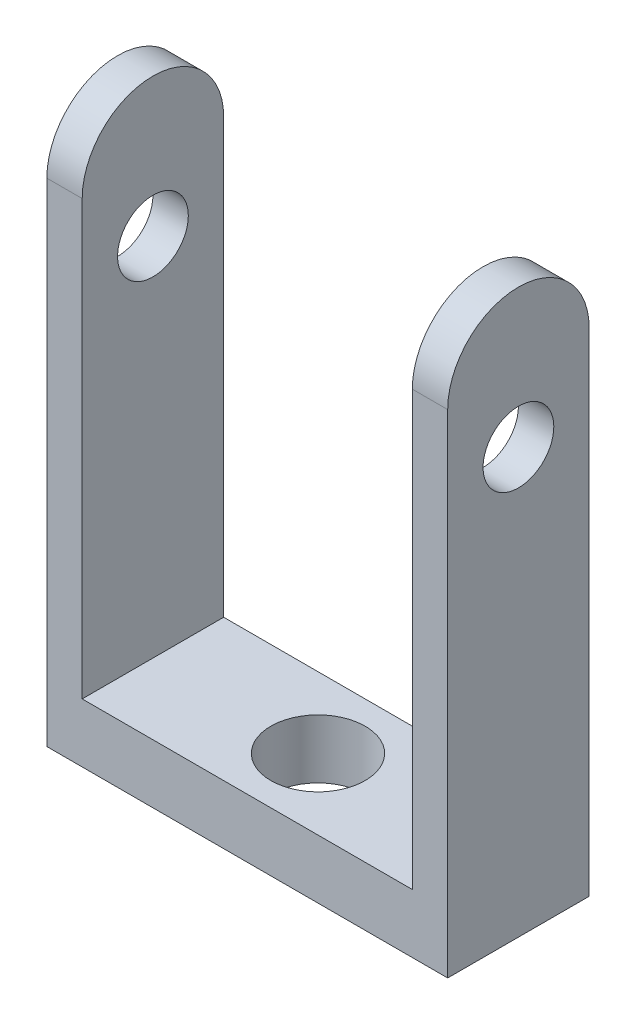
SolidWorks part; units mm, degrees
material "Plain Carbon Steel"
ref_plane "Front Plane" through (0, 0, 0) normal (0, 0, 1) x (1, 0, 0)
ref_plane "Top Plane" through (0, 0, 0) normal (0, 1, 0) x (1, 0, 0)
ref_plane "Right Plane" through (0, 0, 0) normal (1, 0, 0) x (0, 0, -1)
sketch "Sketch1" plane through (0, 0, 0) normal (0, 1, 0) x (1, 0, 0)
  line L1 (-17, -6) -> (17, -6)
  line L2 (-17, -6) -> (-17, 6)
  line L3 (-17, 6) -> (17, 6)
  line L4 (17, -6) -> (17, 6)
  line L5 (0, 6) -> (0, -6) construction
  line L6 (-17, 0) -> (17, 0) construction
  point P1 (0, 0)
  dimension "D1" = 12
  dimension "D2" = 34
extrude "Boss-Extrude1" add sketch "Sketch1" along normal blind 5
sketch "Sketch3" plane through (0, 0, 0) normal (1, 0, 0) x (0, 0, -1)
  line L0 (0, 0) -> (0, 16.3575) construction
sketch3d "3DSketch1" plane through (0, 0, 0) normal (0, 0, 1) x (1, 0, 0)
  dimension "D1" = 17
sketch "Sketch5" plane through (17, 0, 0) normal (1, 0, 0) x (0, 0, -1)
  line L0 (6.6, 0) -> (-6.6, 0) construction
  line L1 (-6, 5) -> (6, 5)
  line L2 (-6, 5) -> (-6, 36)
  line L4 (6, 5) -> (6, 36)
  line L5 (-6, 36) -> (-6, 41.7522)
  line L7 (6, 41.7522) -> (6, 36)
  circle A1 centre (0, 36) radius 3
  arc A2 (-6, 41.7522) -> (6, 41.7522) centre (0, 41.7522) cw
  dimension "D2" = 6
  dimension "D1" = 36
  dimension "D3" = 12
extrude "Boss-Extrude3" add sketch "Sketch5" against normal blind 3
sketch "Sketch6" plane through (0, 5, 0) normal (0, 1, 0) x (1, 0, 0)
  circle A0 centre (0, 0) radius 1.5
  dimension "D1" = 3
extrude "Cut-Extrude1" cut sketch "Sketch6" against normal blind 3
sketch "Sketch7" plane through (14, 0, 0) normal (-1, 0, 0) x (0, 0, 1)
  circle A0 centre (0, 36) radius 4
  dimension "D1" = 8
sketch "Sketch8" plane through (0, 5, 0) normal (0, 1, 0) x (1, 0, 0)
  circle A0 centre (0, 0) radius 4
  dimension "D1" = 8
extrude "Cut-Extrude4" cut sketch "Sketch8" against normal through all
mirror "Mirror1" about plane through (0, 0, 0) normal (1, 0, 0) of "Boss-Extrude3"
